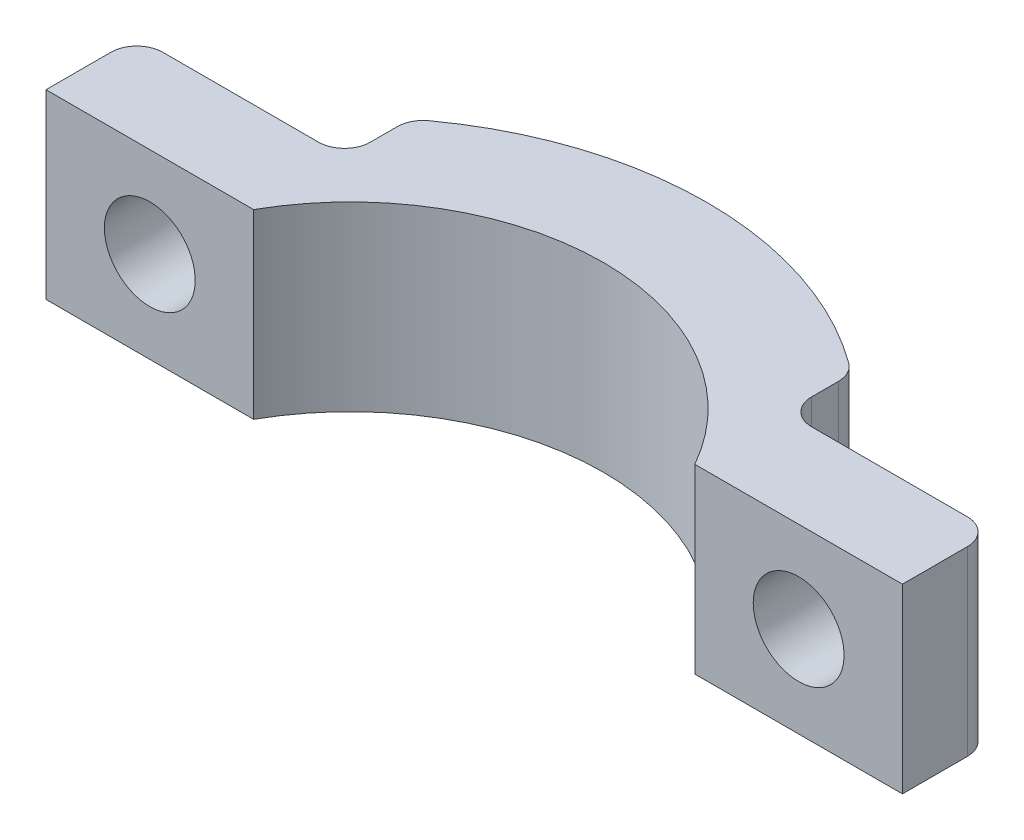
SolidWorks part; units mm, degrees
ref_plane "Front Plane" through (0, 0, 0) normal (0, 0, 1) x (1, 0, 0)
ref_plane "Top Plane" through (0, 0, 0) normal (0, 1, 0) x (1, 0, 0)
ref_plane "Right Plane" through (0, 0, 0) normal (1, 0, 0) x (0, 0, -1)
sketch "Sketch1" plane through (0, 0, 0) normal (0, 1, 0) x (1, 0, 0)
  line L0 (0, 0) -> (-8, 0)
  line L4 (25, 0) -> (17, 0)
  line L5 (-8, 0) -> (-8, 3.5)
  line L6 (-8, 3.5) -> (-2.4803, 3.5)
  line L7 (25, 0) -> (25, 3.5)
  line L8 (25, 3.5) -> (19.4803, 3.5)
  arc A0 (0, 0) -> (17, 0) centre (8.5, -4.7762) cw
  arc A1 (19.4803, 3.5) -> (-2.4803, 3.5) centre (8.5, -4.7762) ccw
  point P5 (0, 0)
  dimension "D3" = 9.75
  dimension "D4" = 13.75
  dimension "D1" = 17
  dimension "D2" = 33
  dimension "D5" = 3.5
extrude "Boss-Extrude1" add sketch "Sketch1" along normal blind 7
ref_plane "Plane1" through (0, 0, -8.9738) normal (0, 0, -1) x (-1, 0, 0)
sketch "Sketch4" plane through (0, 0, -8.9738) normal (0, 0, -1) x (-1, 0, 0)
  line L12 (-19.4803, 0) -> (2.4803, 0) construction
  line L13 (-25, 7) -> (-17, 7)
  line L14 (-25, 7) -> (-25, 0)
  line L15 (-25, 0) -> (-17, 0)
  line L16 (-17, 7) -> (-17, 0)
  line L18 (8, 7) -> (0, 7)
  line L19 (8, 7) -> (8, 0)
  line L20 (8, 0) -> (0, 0)
  line L21 (0, 7) -> (0, 0)
  dimension "D1" = 8
extrude "Cut-Extrude5" cut sketch "Sketch4" against normal up to surface (5.4738 mm away) up to face at (22.2401, 3.5, -3.5)
sketch "Sketch7" plane through (0, 0, -3.5) normal (0, 0, -1) x (-1, 0, 0)
  line L0 (-21, 3.5) -> (-25, 3.5) construction
  line L1 (-25, 7) -> (-25, 0) construction
  line L2 (4, 3.511) -> (8, 3.5) construction
  line L3 (8, 7) -> (8, 0) construction
  circle A0 centre (-21, 3.5) radius 1.75
  circle A1 centre (4, 3.511) radius 1.75
  point P4 (0, 0)
  dimension "D2" = 3.5
  dimension "D1" = 25
extrude "Cut-Extrude6" cut sketch "Sketch7" against normal up to next
fillet "Fillet3" radius 1 6 edges at (-8, 3.5, -3.5) (25, 3.5, -3.5) (17, 3.5, -6.0317) (0, 3.5, -6.0317) (0, 3.5, -3.5) (17, 3.5, -3.5)
